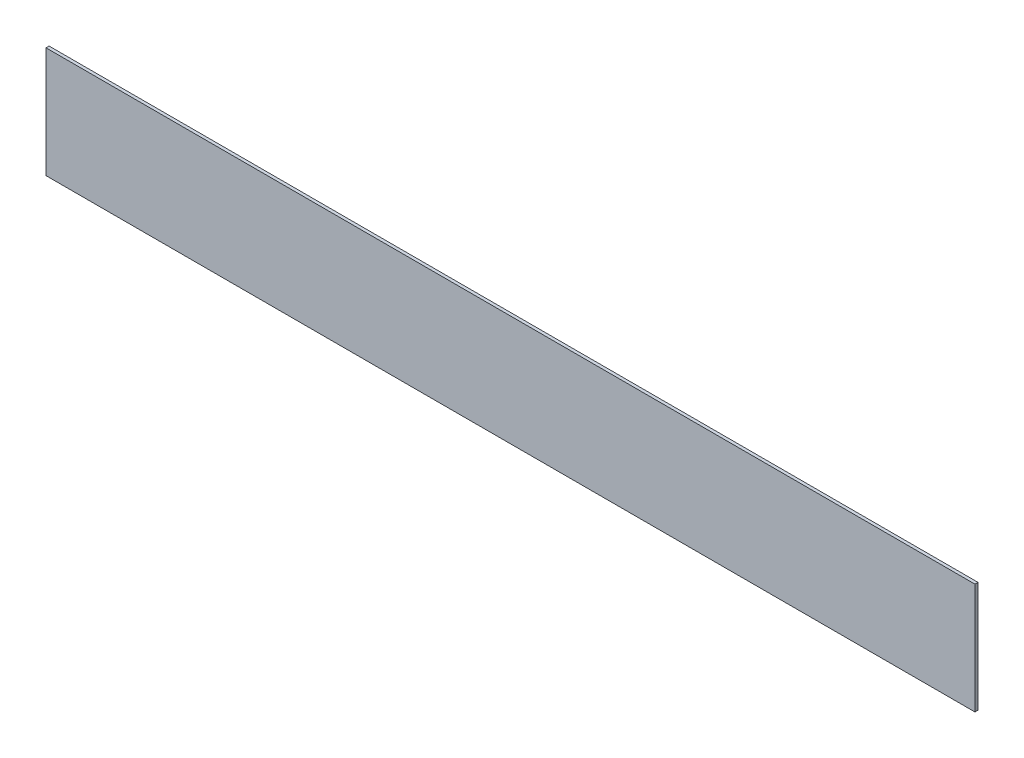
SolidWorks part; units mm, degrees
ref_plane "Front Plane" through (0, 0, 0) normal (0, 0, 1) x (1, 0, 0)
ref_plane "Top Plane" through (0, 0, 0) normal (0, 1, 0) x (1, 0, 0)
ref_plane "Right Plane" through (0, 0, 0) normal (1, 0, 0) x (0, 0, -1)
other "Configuration Table"
sketch "Sketch1" plane through (0, 0, 0) normal (0, 0, 1) x (1, 0, 0)
  line L1 (158, 32) -> (460, 32)
  line L2 (158, 32) -> (158, 68)
  line L3 (158, 68) -> (460, 68)
  line L4 (460, 32) -> (460, 68)
extrude "CEK_taze_kulp_cukuru_1.0_1" add sketch "Sketch1" along normal blind 1 from offset 26 separate body
